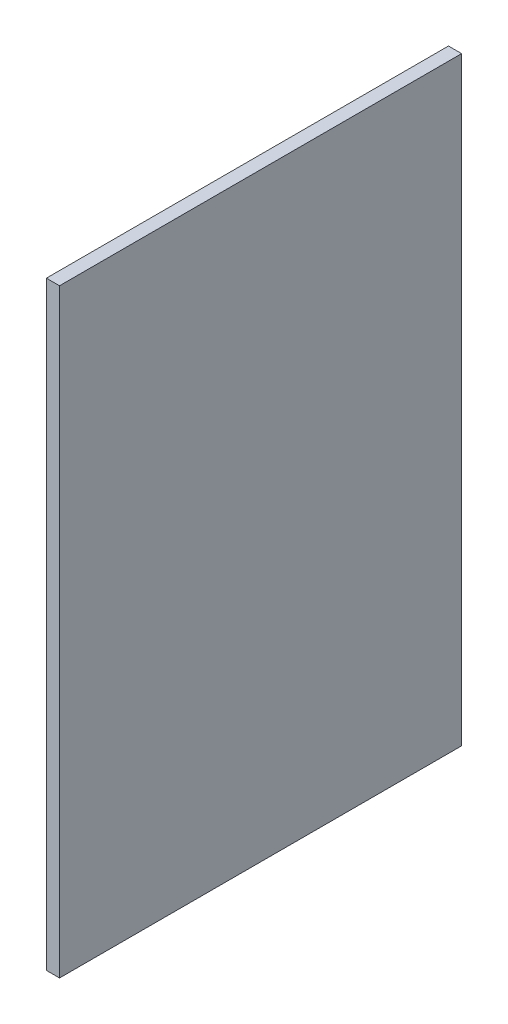
SolidWorks part; units mm, degrees
material "Maple"
ref_plane "Front Plane" through (0, 0, 0) normal (0, 0, 1) x (1, 0, 0)
ref_plane "Top Plane" through (0, 0, 0) normal (0, 1, 0) x (1, 0, 0)
ref_plane "Right Plane" through (0, 0, 0) normal (1, 0, 0) x (0, 0, -1)
sketch "Sketch1" plane through (0, 0, 0) normal (1, 0, 0) x (0, 0, -1)
  line L1 (-275, 410) -> (275, 410)
  line L2 (-275, 410) -> (-275, -410)
  line L3 (-275, -410) -> (275, -410)
  line L4 (275, 410) -> (275, -410)
  line L5 (-275, 410) -> (275, -410) construction
  line L6 (-275, -410) -> (275, 410) construction
  point P0 (0, 0)
  dimension "D1" = 820
  dimension "D2" = 550
extrude "Boss-Extrude1" add sketch "Sketch1" along normal blind 18
